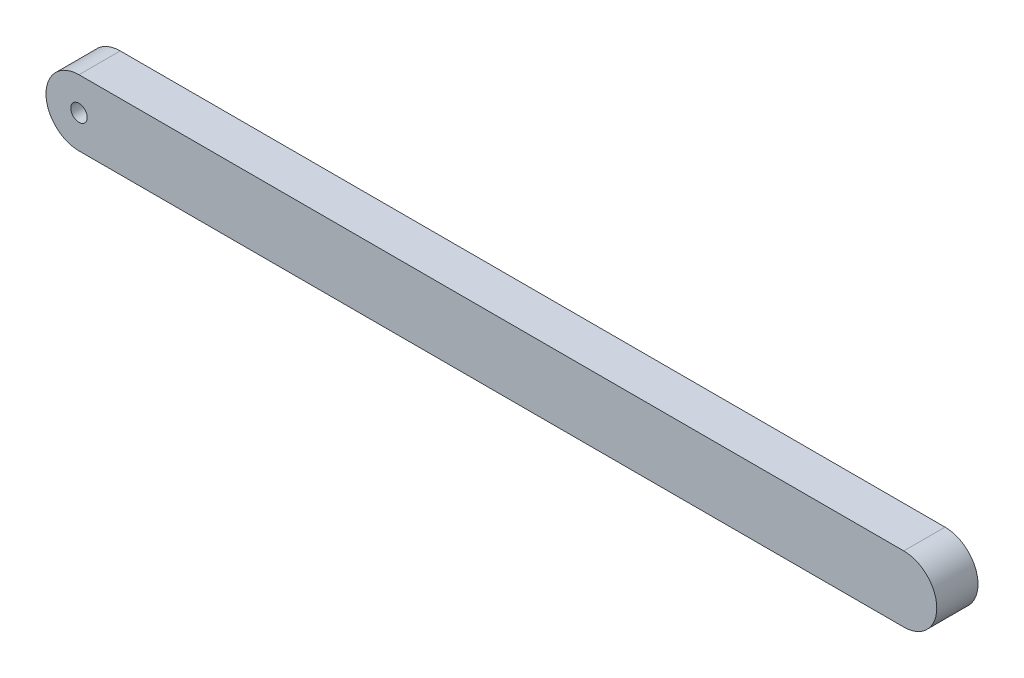
SolidWorks part; units mm, degrees
ref_plane "Front Plane" through (0, 0, 0) normal (0, 0, 1) x (1, 0, 0)
ref_plane "Top Plane" through (0, 0, 0) normal (0, 1, 0) x (1, 0, 0)
ref_plane "Right Plane" through (0, 0, 0) normal (1, 0, 0) x (0, 0, -1)
sketch "Sketch2" plane through (0, 0, 0) normal (0, 0, 1) x (1, 0, 0)
  line L0 (0, 0) -> (1000, 0) construction
  line L1 (0, 40) -> (1000, 40)
  line L2 (0, -40) -> (1000, -40)
  arc A0 (0, 40) -> (0, -40) centre (0, 0) ccw
  arc A1 (1000, -40) -> (1000, 40) centre (1000, 0) ccw
  circle A2 centre (0, 0) radius 10
  point P3 (500, 0)
  dimension "D2" = 40
  dimension "D3" = 20
  dimension "D1" = 1000
extrude "Boss-Extrude1" add sketch "Sketch2" against normal blind 50
